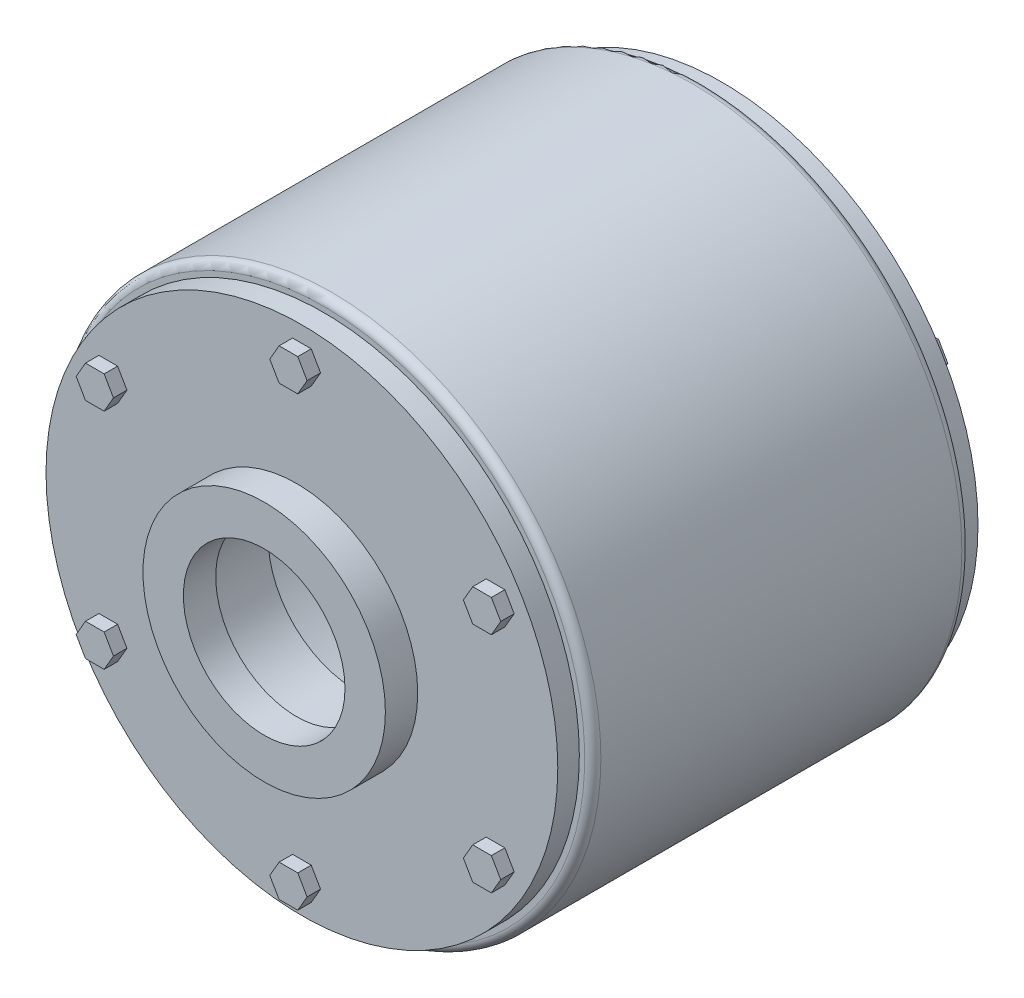
SolidWorks part; units mm, degrees
ref_plane "前视基准面" through (0, 0, 0) normal (0, 0, 1) x (1, 0, 0)
ref_plane "上视基准面" through (0, 0, 0) normal (0, 1, 0) x (1, 0, 0)
ref_plane "右视基准面" through (0, 0, 0) normal (1, 0, 0) x (0, 0, -1)
sketch "草图1" plane through (0, 0, 0) normal (1, 0, 0) x (0, 0, -1)
  line L0 (-1000, 0) -> (49000, 0) construction
  line L1 (-70, 100) -> (0, 100)
  line L4 (0, 100) -> (0, 58)
  line L5 (0, 58) -> (-9.5, 58)
  line L6 (-9.5, 58) -> (-9.5, 70)
  line L7 (-9.5, 70) -> (-70, 70)
  line L8 (-70, 70) -> (-70, 100)
  line L9 (0, -1000) -> (0, 49000) construction
  dimension "D1" = 100
  dimension "D2" = 70
  dimension "D3" = 58
  dimension "D4" = 70
  dimension "D5" = 9.5
revolve "旋转2" add sketch "草图1" angle 360 about L0
sketch "草图2" plane through (0, 0, 70) normal (0, 0, 1) x (1, 0, 0)
  circle A0 centre (0, 0) radius 57
  circle A1 centre (0, 0) radius 70
  circle A2 centre (0, 0) radius 70 construction
  dimension "D1" = 114
extrude "凸台-拉伸1" add sketch "草图2" against normal blind 12 separate body
sketch "草图3" plane through (0, 0, 70) normal (0, 0, 1) x (1, 0, 0)
  circle A0 centre (0, 0) radius 40
  circle A1 centre (0, 0) radius 57
  circle A2 centre (0, 0) radius 57 construction
  dimension "D1" = 80
extrude "凸台-拉伸2" add sketch "草图3" against normal blind 7
sketch "草图4" plane through (0, 0, 70) normal (0, 0, 1) x (1, 0, 0)
  circle A0 centre (0, 0) radius 95
  circle A1 centre (0, 0) radius 40
  circle A2 centre (0, 0) radius 40 construction
  dimension "D1" = 190
extrude "凸台-拉伸3" add sketch "草图4" along normal blind 8
sketch "草图5" plane through (0, 0, 78) normal (0, 0, 1) x (1, 0, 0)
  line L1 (3.4641, 77) -> (6.9282, 83)
  line L2 (6.9282, 83) -> (3.4641, 89)
  line L3 (3.4641, 89) -> (-3.4641, 89)
  line L4 (-3.4641, 89) -> (-6.9282, 83)
  line L5 (-6.9282, 83) -> (-3.4641, 77)
  line L6 (-3.4641, 77) -> (3.4641, 77)
  circle A0 centre (0, 83) radius 6 construction
  dimension "D1" = 12
  dimension "D2" = 83
extrude "凸台-拉伸4" add sketch "草图5" along normal blind 5
pattern_circular "阵列(圆周)2" count 6 over 360 about axis through (0, 0, 0) along (0, 0, 1) of "凸台-拉伸4"
fillet "圆角1" radius 3 1 edges at (100, 0, 70)
mirror "镜向8" about plane through (0, 100, 0) normal (0, 0, 1) of bodies 117
ref_plane "基准面1" through (0, 0, 80) normal (0, 0, 1) x (1, 0, 0)
sketch "草图6" plane through (0, 0, 80) normal (0, 0, 1) x (1, 0, 0)
  circle A0 centre (0, 0) radius 40
  circle A1 centre (0, 0) radius 40 construction
  circle A2 centre (0, 0) radius 32.5
  dimension "D1" = 65
extrude "凸台-拉伸5" add sketch "草图6" against normal blind 22
sketch "草图7" plane through (0, 0, 80) normal (0, 0, 1) x (1, 0, 0)
  circle A0 centre (0, 0) radius 30
  circle A1 centre (0, 0) radius 45
  circle A2 centre (0, 0) radius 32.5 construction
  dimension "D1" = 90
  dimension "D2" = 60
extrude "凸台-拉伸6" add sketch "草图7" along normal blind 12
